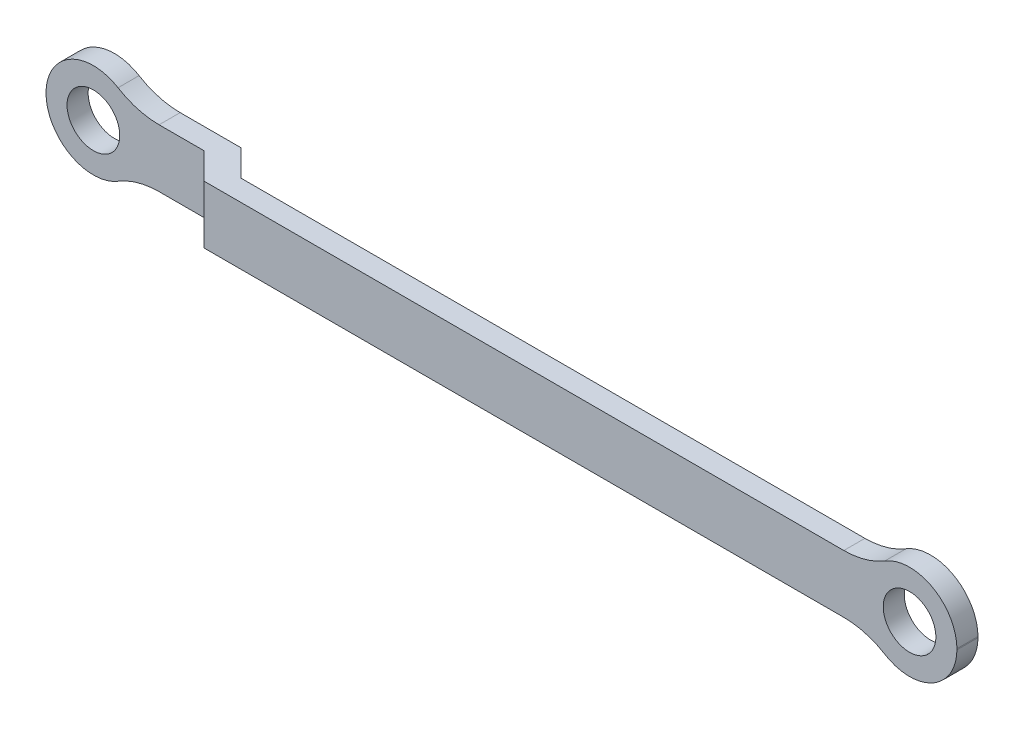
SolidWorks part; units mm, degrees
ref_plane "前视基准面" through (0, 0, 0) normal (0, 0, 1) x (1, 0, 0)
ref_plane "上视基准面" through (0, 0, 0) normal (0, 1, 0) x (1, 0, 0)
ref_plane "右视基准面" through (0, 0, 0) normal (1, 0, 0) x (0, 0, -1)
sketch "草图2" plane through (0, 0, 0) normal (0, 0, 1) x (1, 0, 0)
  line B0 (147.5199, 5.5022) -> (12.4799, 5.5002)
  line B1 (12.4801, -5.4998) -> (147.5201, -5.4978)
  line B2 (-8.9994, 0.0999) -> (-8.9994, -0.1001)
  line B3 (168.9994, 0.1025) -> (168.9994, -0.0974)
  arc B4 (12.4801, -5.4998) -> (4.6801, -7.6874) centre (12.4803, -20.4998) ccw
  arc B5 (4.6799, 7.6876) -> (-8.9994, 0.0999) centre (0, 0) ccw
  arc B6 (-8.9994, -0.1001) -> (4.6801, -7.6874) centre (0, 0) ccw
  arc B7 (4.6799, 7.6876) -> (12.4799, 5.5002) centre (12.4797, 20.5002) ccw
  arc B8 (147.5199, 5.5022) -> (155.3199, 7.6898) centre (147.5197, 20.5022) ccw
  arc B9 (155.3201, -7.6852) -> (168.9994, -0.0974) centre (160, 0.0024) ccw
  arc B10 (168.9994, 0.1025) -> (155.3199, 7.6898) centre (160, 0.0024) ccw
  arc B11 (155.3201, -7.6852) -> (147.5201, -5.4978) centre (147.5203, -20.4978) ccw
  circle B12 centre (0, 0) radius 5
  circle B13 centre (160, 0.0024) radius 2
sketch_block_instance "块1-1"
sketch_block "块1"
extrude "凸台-拉伸1" add sketch "草图2" along normal blind 9
sketch "草图3" plane through (-0.0001, 5.5, 0) normal (0, 1, 0) x (1, 0, 0)
  line L0 (21.0006, -4) -> (26.0006, -9)
  line L1 (-8.9994, -9) -> (26.0006, -9)
  line L2 (-8.9994, -9) -> (-8.9994, -4)
  line L3 (-8.9994, -4) -> (21.0006, -4)
  line L4 (29.0006, -5) -> (24.0006, 0)
  line L5 (168.9994, 0) -> (24.0006, 0)
  line L6 (168.9994, 0) -> (168.9994, -5)
  line L7 (168.9994, -5) -> (29.0006, -5)
  line L9 (147.52, -9) -> (12.48, -9) construction
  line L10 (147.52, 0) -> (12.48, 0) construction
  dimension "D1" = 5
  dimension "D2" = 45
  dimension "D3" = 30
  dimension "D4" = 5
  dimension "D5" = 135
  dimension "D6" = 3
extrude "切除-拉伸1" cut sketch "草图3" against normal through all and the other way through all
sketch "草图4" plane through (0, 0, 9) normal (0, 0, 1) x (1, 0, 0)
  circle A0 centre (160, 0.0024) radius 5
  dimension "D1" = 10
extrude "切除-拉伸2" cut sketch "草图4" against normal through all
